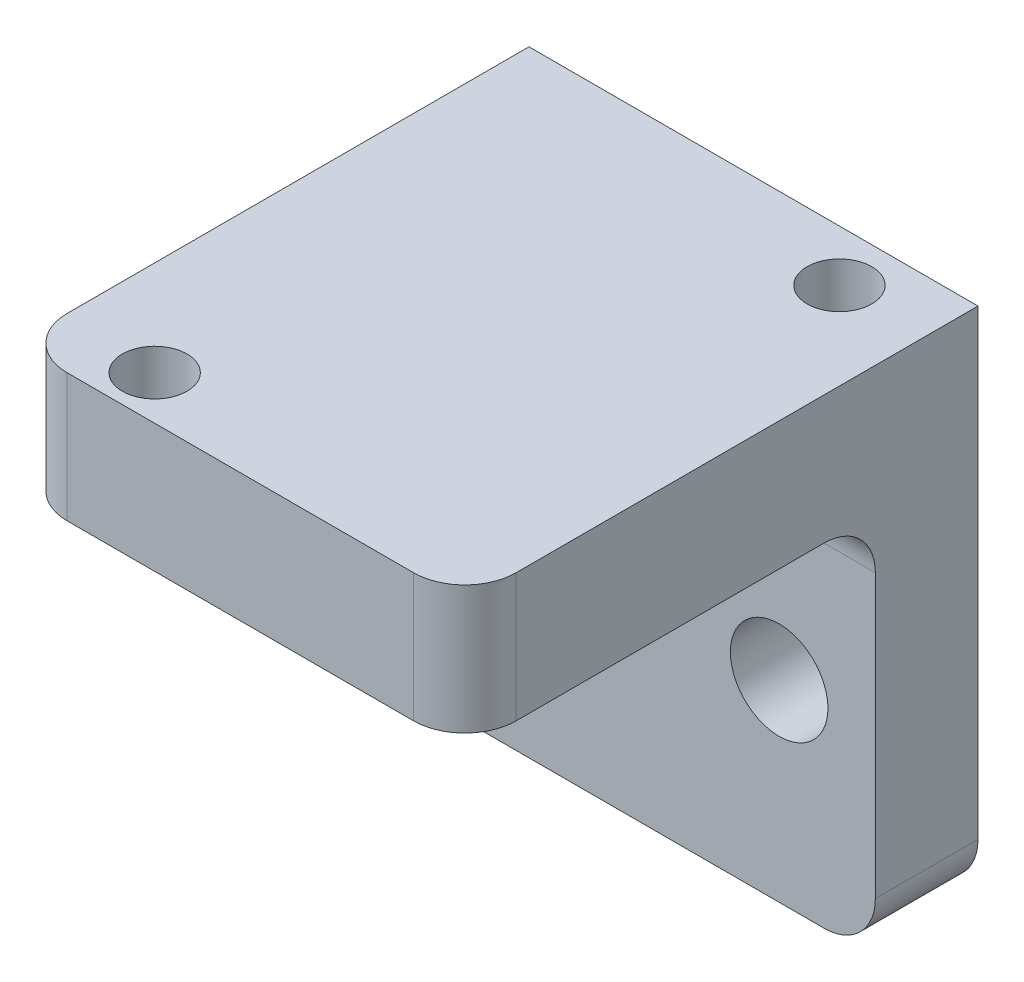
SolidWorks part; units mm, degrees
ref_plane "Front Plane" through (0, 0, 0) normal (0, 0, 1) x (1, 0, 0)
ref_plane "Top Plane" through (0, 0, 0) normal (0, 1, 0) x (1, 0, 0)
ref_plane "Right Plane" through (0, 0, 0) normal (1, 0, 0) x (0, 0, -1)
sketch "Sketch1" plane through (0, 0, 0) normal (0, 1, 0) x (1, 0, 0)
  line L0 (10.16, 10.16) -> (-3.0442, -10.5294) construction
  line L2 (10.16, -10.16) -> (10.16, 10.16) construction
  line L3 (10.16, 10.16) -> (-10.16, 10.16) construction
  line L5 (0, 10.16) -> (0, -5.207) construction
  line L6 (10.16, 0) -> (-3.429, 0) construction
  line L7 (-7.747, -12.7) -> (14.478, -12.7)
  line L8 (-7.747, -12.7) -> (-7.747, 12.7)
  line L9 (-7.747, 12.7) -> (14.478, 12.7)
  line L10 (14.478, -12.7) -> (14.478, 12.7)
  line L11 (3.3655, 12.7) -> (3.3655, -12.7) construction
  line L12 (-7.747, 0) -> (14.478, 0) construction
  circle A0 centre (10.16, 10.16) radius 1.6002
  circle A1 centre (-3.0442, -10.5294) radius 1.6002
  point P0 (0, 0)
  point P6 (3.3655, 0)
  point P13 (-11.1125, -5.207)
  point P14 (-11.1125, -5.207)
  point P15 (2.5878, -17.8089)
  point P16 (-2.0917, -10.5294)
  dimension "D1" = 20.32
  dimension "D3" = 3.2004
  dimension "D4" = 25.4
  dimension "D2" = 20.32
  dimension "D5" = 22.225
  dimension "D6" = 24.5439
extrude "Boss-Extrude1" add sketch "Sketch1" against normal blind 6.35
sketch "Sketch2" plane through (0, 0, -12.7) normal (0, 0, -1) x (-1, 0, 0)
  line L0 (7.747, -6.35) -> (7.747, 0) construction
  line L1 (-14.478, -6.35) -> (7.747, -6.35)
  line L2 (-14.478, -6.35) -> (-14.478, -25.4)
  line L3 (-14.478, -25.4) -> (7.747, -25.4)
  line L4 (7.747, -6.35) -> (7.747, -25.4)
  line L5 (-3.3655, -25.4) -> (-3.3655, -6.35) construction
  line L6 (-14.478, -15.875) -> (7.747, -15.875) construction
  circle A0 centre (-9.7155, -15.875) radius 2.413
  circle A1 centre (2.9845, -15.875) radius 2.413
  point P116 (-3.3655, -15.875)
  dimension "D2" = 4.826
  dimension "D3" = 12.7
  dimension "D1" = 19.05
extrude "Boss-Extrude2" add sketch "Sketch2" against normal blind 5.08
fillet "Fillet1" radius 2.54 5 edges at (14.478, -25.4, -10.16) (-7.747, -25.4, -10.16) (14.478, -3.175, 12.7) (-7.747, -3.175, 12.7) (3.3655, -6.35, -7.62)
